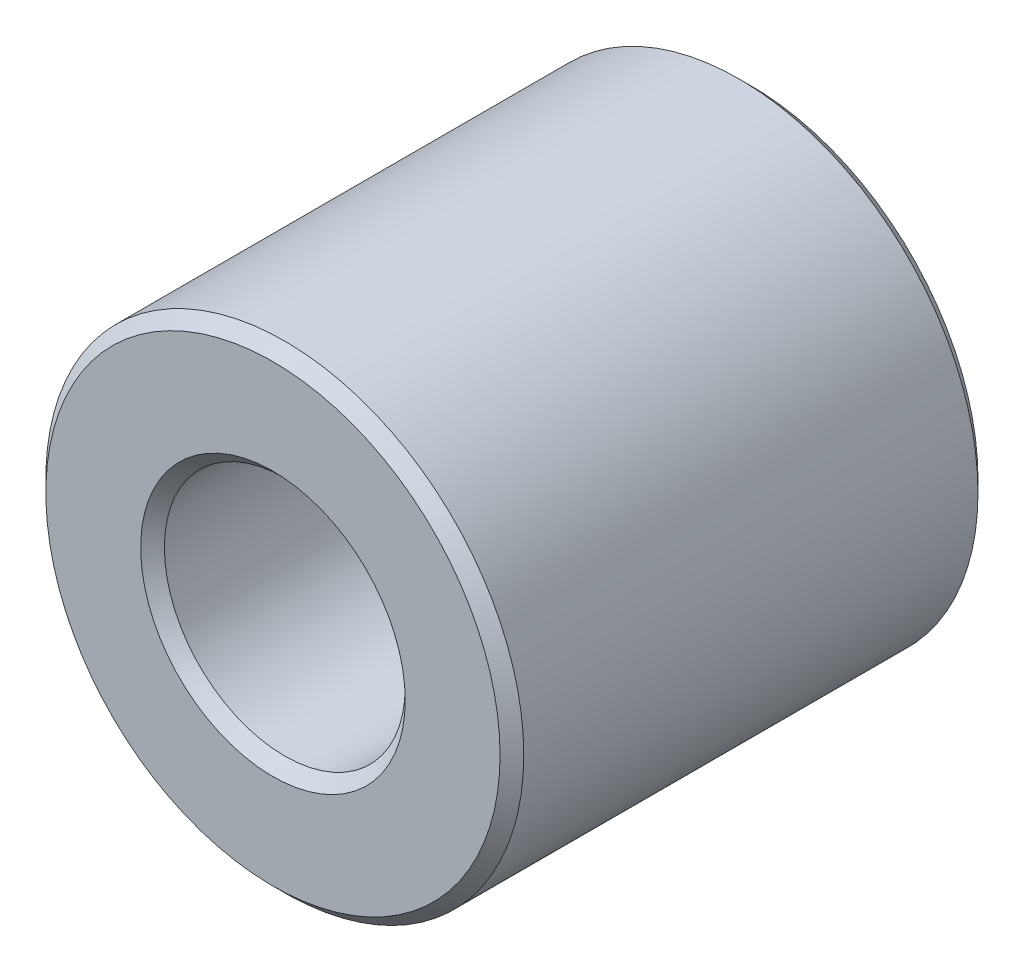
SolidWorks part; units mm, degrees
ref_plane "Front Plane" through (0, 0, 0) normal (0, 0, 1) x (1, 0, 0)
ref_plane "Top Plane" through (0, 0, 0) normal (0, 1, 0) x (1, 0, 0)
ref_plane "Right Plane" through (0, 0, 0) normal (1, 0, 0) x (0, 0, -1)
sketch "Sketch1" plane through (0, 0, 0) normal (0, 0, 1) x (1, 0, 0)
  circle A0 centre (0, 0) radius 6.35 construction
  circle A1 centre (0, 0) radius 3.2004 construction
  point P4 (0, 6.35)
  dimension "ID" = 6.4008
  dimension "OD" = 12.7
sketch "Sketch2" plane through (0, 0, 0) normal (1, 0, 0) x (0, 0, -1)
  line L0 (-6.35, 6.35) -> (6.35, 6.35) construction
  dimension "Length" = 12.7
sketch "Sketch3" plane through (0, 0, 0) normal (0, 0, 1) x (1, 0, 0)
  circle A0 centre (0, 0) radius 3.2004 construction
  circle A1 centre (0, 0) radius 6.35 construction
  circle A2 centre (0, 0) radius 3.2004
  circle A3 centre (0, 0) radius 6.35
extrude "Boss-Extrude1" add sketch "Sketch3" against normal up to vertex (6.35 mm away) and the other way up to vertex (6.35 mm away) up to point (0, 6.35, -6.35) other way up to point (0, 6.35, 6.35)
chamfer "Chamfer1" distance 0.315 angle 45 4 edges at (6.35, 0, 6.35) (6.35, 0, -6.35) (3.2004, 0, 6.35) (3.2004, 0, -6.35)
equation "\"D1@Chamfer1\"=(\"OD@Sketch1\"-\"ID@Sketch1\")*0.05"
equation "\"Length\"= 0.5in"
equation "\"Length@Sketch2\"= \"Length\""
